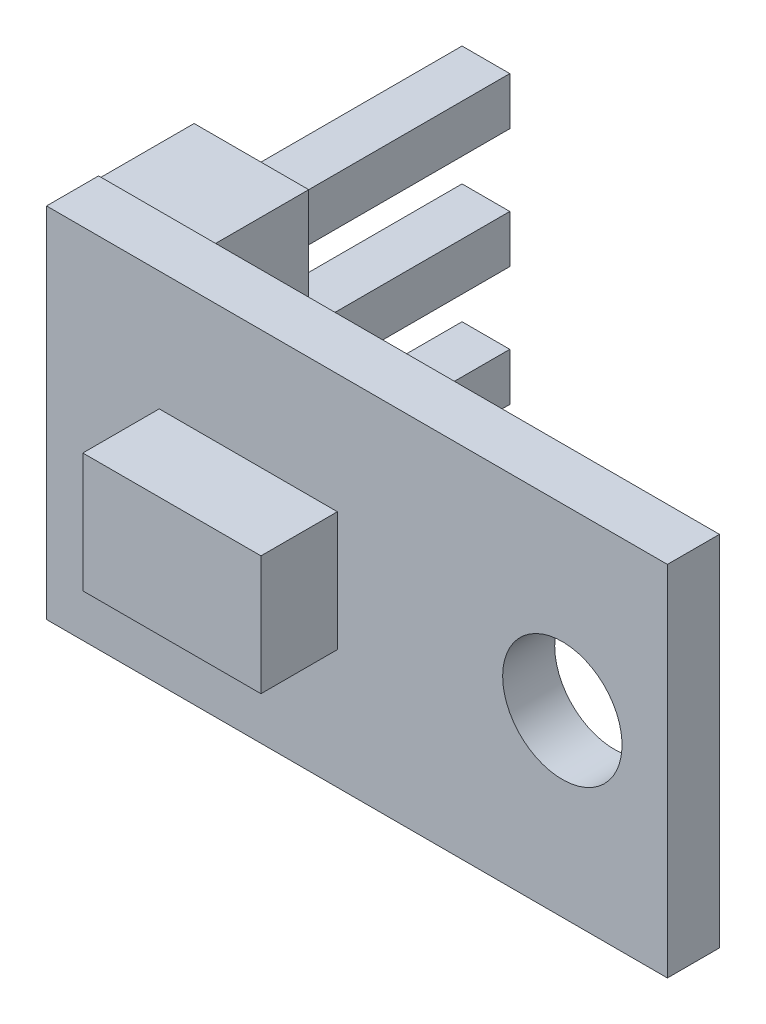
SolidWorks part; units mm, degrees
ref_plane "Plan de face" through (0, 0, 0) normal (0, 0, 1) x (1, 0, 0)
ref_plane "Plan de dessus" through (0, 0, 0) normal (0, 1, 0) x (1, 0, 0)
ref_plane "Plan de droite" through (0, 0, 0) normal (1, 0, 0) x (0, 0, -1)
sketch "Esquisse1" plane through (0, 0, 0) normal (0, 0, 1) x (1, 0, 0)
  line L0 (-29.2958, 7.5) -> (-16.2958, 7.5)
  line L1 (-16.2958, 7.5) -> (-16.2958, 0)
  line L2 (-16.2958, 0) -> (-29.2958, 0)
  line L3 (-29.2958, 0) -> (-29.2958, 7.5)
  dimension "D1" = 13
  dimension "D2" = 7.5
extrude "Boss.-Extru.3" add sketch "Esquisse1" along normal blind 1.09
sketch "Esquisse4" plane through (0, 0, 1.09) normal (0, 0, 1) x (1, 0, 0)
  line L0 (-26.9358, 5) -> (-23.2058, 5)
  line L1 (-23.2058, 5) -> (-23.2058, 2.5)
  line L2 (-23.2058, 2.5) -> (-26.9358, 2.5)
  line L3 (-26.9358, 2.5) -> (-26.9358, 5)
  line L4 (-29.2958, 7.5) -> (-29.2958, 0) construction
  line L5 (-16.2958, 0) -> (-16.2958, 7.5) construction
  line L6 (-16.2958, 7.5) -> (-29.2958, 7.5) construction
  line L7 (-29.2958, 0) -> (-16.2958, 0) construction
  dimension "D1" = 2.36
  dimension "D2" = 6.91
  dimension "D3" = 2.5
  dimension "D4" = 2.5
  dimension "D5" = 2.5
  dimension "D6" = 3.73
extrude "Boss.-Extru.4" add sketch "Esquisse4" along normal blind 1.6
sketch "Esquisse5" plane through (0, 0, 1.09) normal (0, 0, 1) x (1, 0, 0)
  line L0 (-28.0958, 5.75) -> (-28.0958, 4.25) construction
  line L1 (-28.5958, 6.75) -> (-27.5958, 6.75)
  line L2 (-28.5958, 6.75) -> (-28.5958, 5.75)
  line L3 (-28.5958, 5.75) -> (-27.5958, 5.75)
  line L4 (-27.5958, 6.75) -> (-27.5958, 5.75)
  line L5 (-28.5958, 4.25) -> (-27.5958, 4.25)
  line L6 (-28.5958, 4.25) -> (-28.5958, 3.25)
  line L7 (-28.5958, 3.25) -> (-27.5958, 3.25)
  line L8 (-27.5958, 4.25) -> (-27.5958, 3.25)
  line L9 (-28.5958, 1.75) -> (-27.5958, 1.75)
  line L10 (-28.5958, 1.75) -> (-28.5958, 0.75)
  line L11 (-28.5958, 0.75) -> (-27.5958, 0.75)
  line L12 (-27.5958, 1.75) -> (-27.5958, 0.75)
  line L13 (-28.0958, 4.25) -> (-28.0958, 3.25) construction
  line L14 (-28.0958, 3.25) -> (-28.0958, 1.75) construction
  line L15 (-28.5958, 3.75) -> (-29.2958, 3.75) construction
  line L16 (-29.2958, 7.5) -> (-29.2958, 0) construction
  dimension "D1" = 1
  dimension "D2" = 0.7
  dimension "D3" = 1.5
extrude "Boss.-Extru.5" add sketch "Esquisse5" against normal blind 8
sketch "Esquisse6" plane through (0, 0, 0) normal (0, 0, -1) x (-1, 0, 0)
  line L0 (28.5958, 5.75) -> (28.5958, 6.75) construction
  line L1 (28.5958, 6.75) -> (27.5958, 6.75) construction
  line L2 (27.5958, 6.75) -> (27.5958, 5.75) construction
  line L3 (27.5958, 5.75) -> (28.5958, 5.75) construction
  line L4 (28.5958, 3.25) -> (28.5958, 4.25) construction
  line L5 (28.5958, 4.25) -> (27.5958, 4.25) construction
  line L6 (27.5958, 4.25) -> (27.5958, 3.25) construction
  line L7 (27.5958, 3.25) -> (28.5958, 3.25) construction
  line L8 (28.5958, 0.75) -> (28.5958, 1.75) construction
  line L9 (28.5958, 1.75) -> (27.5958, 1.75) construction
  line L10 (27.5958, 1.75) -> (27.5958, 0.75) construction
  line L11 (27.5958, 0.75) -> (28.5958, 0.75) construction
  line L12 (28.5958, 5.75) -> (28.5958, 6.75)
  line L13 (28.5958, 6.75) -> (27.5958, 6.75)
  line L14 (27.5958, 6.75) -> (27.5958, 5.75)
  line L15 (27.5958, 5.75) -> (28.5958, 5.75)
  line L16 (28.5958, 3.25) -> (28.5958, 4.25)
  line L17 (28.5958, 4.25) -> (27.5958, 4.25)
  line L18 (27.5958, 4.25) -> (27.5958, 3.25)
  line L19 (27.5958, 3.25) -> (28.5958, 3.25)
  line L20 (28.5958, 0.75) -> (28.5958, 1.75)
  line L21 (28.5958, 1.75) -> (27.5958, 1.75)
  line L22 (27.5958, 1.75) -> (27.5958, 0.75)
  line L23 (27.5958, 0.75) -> (28.5958, 0.75)
  line L24 (29.2958, 5.05) -> (29.2958, 7.45)
  line L25 (29.2958, 7.45) -> (26.8958, 7.45)
  line L26 (26.8958, 7.45) -> (26.8958, 5.05)
  line L27 (26.8958, 5.05) -> (29.2958, 5.05)
  line L28 (29.2958, 2.55) -> (29.2958, 4.95)
  line L29 (29.2958, 4.95) -> (26.8958, 4.95)
  line L30 (26.8958, 4.95) -> (26.8958, 2.55)
  line L31 (26.8958, 2.55) -> (29.2958, 2.55)
  line L32 (29.2958, 0.05) -> (29.2958, 2.45)
  line L33 (29.2958, 2.45) -> (26.8958, 2.45)
  line L34 (26.8958, 2.45) -> (26.8958, 0.05)
  line L35 (26.8958, 0.05) -> (29.2958, 0.05)
  dimension "D1" = 0.7
  dimension "D2" = 0.7
  dimension "D3" = 0.7
extrude "Boss.-Extru.6" add sketch "Esquisse6" along normal blind 2 separate body
sketch "Esquisse7" plane through (0, 0, 0) normal (0, 0, -1) x (-1, 0, 0)
  line L0 (18.4958, 3.75) -> (16.2958, 3.75) construction
  line L1 (16.2958, 0) -> (16.2958, 7.5) construction
  circle A0 centre (18.4958, 3.75) radius 1.25
  dimension "D1" = 2.5
  dimension "D2" = 2.2
extrude "Enlèv. mat.-Extru.1" cut sketch "Esquisse7" against normal through all
